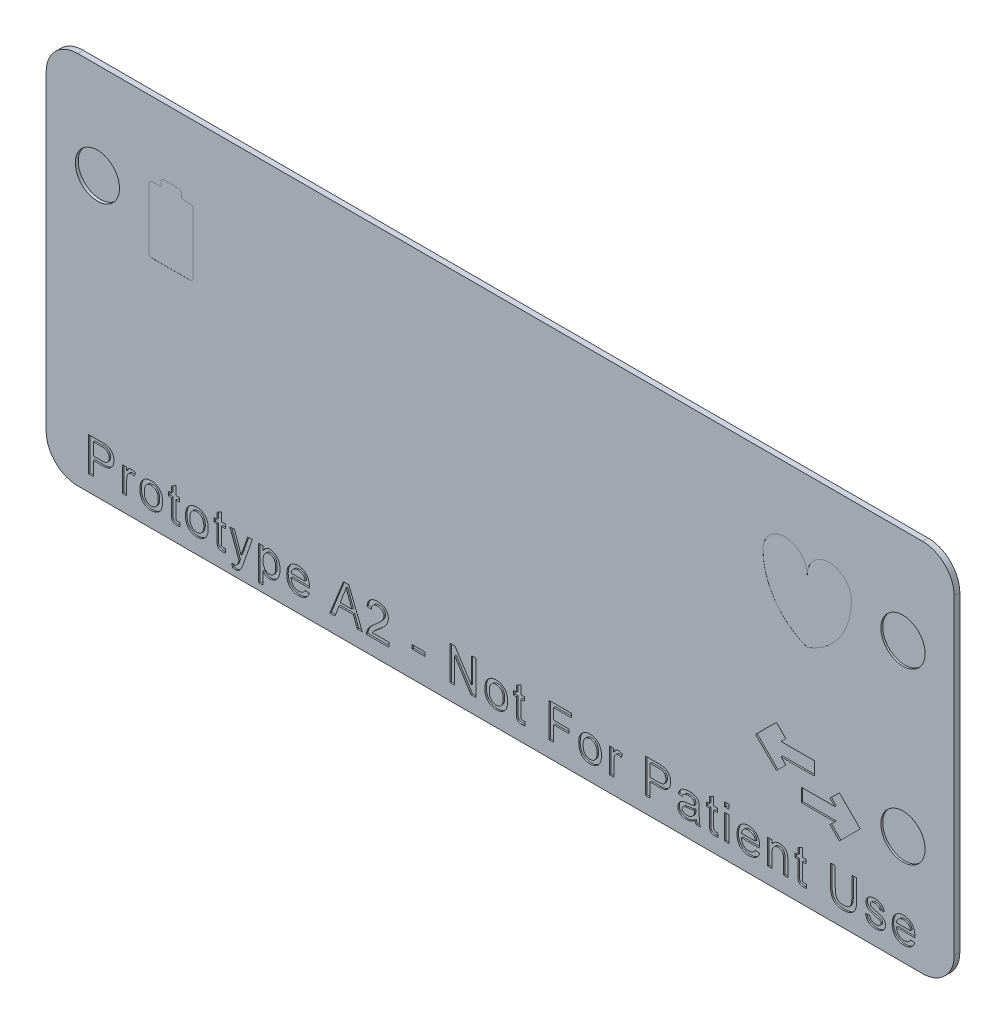
SolidWorks part; units mm, degrees
material "PC High Viscosity"
ref_plane "Front" through (0, 0, 0) normal (0, 0, 1) x (1, 0, 0)
ref_plane "Top" through (0, 0, 0) normal (0, 1, 0) x (1, 0, 0)
ref_plane "Right" through (0, 0, 0) normal (1, 0, 0) x (0, 0, -1)
sketch "Sketch1" plane through (0, 0, 0) normal (0, 0, 1) x (1, 0, 0)
  line L1 (2.14, 0) -> (59.46, 0)
  line L2 (0, 2.14) -> (0, 23.26)
  line L3 (2.14, 25.4) -> (59.46, 25.4)
  line L4 (61.6, 2.14) -> (61.6, 23.26)
  arc A0 (2.14, 0) -> (0, 2.14) centre (2.14, 2.14) cw
  arc A1 (59.46, 0) -> (61.6, 2.14) centre (59.46, 2.14) ccw
  arc A2 (61.6, 23.26) -> (59.46, 25.4) centre (59.46, 23.26) ccw
  arc A3 (2.14, 25.4) -> (0, 23.26) centre (2.14, 23.26) ccw
  point P7 (0, 0)
  point P12 (61.6, 25.4)
  point P15 (0, 25.4)
  dimension "D3" = 2.14
  dimension "D1" = 61.6
  dimension "D2" = 25.4
extrude "Boss-Extrude1" add sketch "Sketch1" along normal blind 0.381
sketch "Sketch2" plane through (0, 0, 0.381) normal (0, 0, 1) x (1, 0, 0)
  line L0 (30.8, 25.4) -> (30.8, 0) construction
  line L2 (2.14, 0) -> (59.46, 0) construction
  line L3 (58.125, 18.8976) -> (58.125, -4.1148) construction
  line L4 (3.475, 18.8976) -> (58.125, 18.8976) construction
  line L5 (48.5461, 7.3914) -> (55.3086, 7.3914) construction
  line L6 (3.475, 30.7351) -> (3.475, 17.3073) construction
  line L7 (59.46, 25.4) -> (2.14, 25.4) construction
  circle A1 centre (58.125, 18.8976) radius 1.5
  circle A2 centre (58.125, 7.3914) radius 1.5
  dimension "D1" = 3
  dimension "D2" = 27.325
  dimension "D3" = 7.3914
  dimension "D4" = 18.8976
  dimension "D5" = 27.325
extrude "Cut-Extrude1" cut sketch "Sketch2" against normal blind 0.127
sketch "Sketch17" plane through (0, 0, 0.381) normal (0, 0, 1) x (1, 0, 0)
  line L0 (30.8, 0) -> (30.8, 22.262) construction
  line L1 (2.14, 0) -> (59.46, 0) construction
  line L2 (58.125, 18.8976) -> (3.475, 18.8976) construction
  line L3 (3.475, 18.8976) -> (3.475, 16.2455) construction
  circle A0 centre (3.475, 18.8976) radius 1.5
  dimension "D2" = 3
  dimension "D1" = 27.325
extrude "Cut-Extrude9" cut sketch "Sketch17" against normal blind 0.2
sketch "Sketch10" plane through (0, 0, 0.381) normal (0, 0, 1) x (1, 0, 0)
  line L0 (51.625, 29.7824) -> (51.625, 19.4976) construction
  line L1 (40.6019, 17.9976) -> (41.1685, 17.9976) construction
  line L2 (43.0868, 17.9976) -> (43.716, 17.9976) construction
  line L3 (51.625, 29.2607) -> (51.625, 15.255) construction
  line L4 (50.125, 19.4976) -> (53.125, 19.4976) construction
  line L5 (48.7156, 18.8976) -> (48.207, 18.8976) construction
  line L6 (58.125, 18.8976) -> (58.125, 26.6614) construction
  arc A0 (51.625, 19.4976) -> (48.625, 19.4976) centre (50.125, 19.4976) ccw
  arc A1 (54.625, 19.4976) -> (51.625, 19.4976) centre (53.125, 19.4976) ccw
  arc A2 (48.625, 19.4976) -> (51.625, 15.255) centre (53.125, 19.4976) ccw
  arc A3 (54.625, 19.4976) -> (51.625, 15.255) centre (50.125, 19.4976) cw
  point P16 (51.625, 19.4976)
  dimension "D3" = 0.6
  dimension "D1" = 1.5
  dimension "D4" = 6.5
extrude "Heart Sym Cut-Extrude6" cut sketch "Sketch10" against normal blind 0.005
sketch "Sketch11" plane through (0, 0, 0.381) normal (0, 0, 1) x (1, 0, 0)
  line L0 (7.175, 20.3976) -> (7.775, 20.3976)
  line L1 (9.175, 20.3976) -> (9.775, 20.3976)
  line L2 (6.975, 20.1976) -> (6.975, 16.0976)
  line L3 (7.175, 15.8976) -> (9.775, 15.8976)
  line L4 (9.975, 20.1976) -> (9.975, 16.0976)
  line L5 (51.625, 15.255) -> (51.625, 14.7576) construction
  line L6 (7.775, 20.3976) -> (7.775, 20.6976)
  line L7 (7.975, 20.8976) -> (8.975, 20.8976)
  line L8 (9.175, 20.3976) -> (9.175, 20.6976)
  line L9 (8.475, 15.8976) -> (8.475, 20.8976) construction
  line L10 (3.475, 18.8976) -> (14.277, 18.8976) construction
  line L11 (8.475, 18.8976) -> (8.475, 24.0535) construction
  line L12 (6.975, 18.3976) -> (9.975, 18.3976) construction
  line L13 (3.475, 18.8976) -> (3.475, 18.4021) construction
  arc A0 (9.975, 16.0976) -> (9.775, 15.8976) centre (9.775, 16.0976) cw
  arc A1 (7.175, 15.8976) -> (6.975, 16.0976) centre (7.175, 16.0976) cw
  arc A2 (9.975, 20.1976) -> (9.775, 20.3976) centre (9.775, 20.1976) ccw
  arc A3 (6.975, 20.1976) -> (7.175, 20.3976) centre (7.175, 20.1976) cw
  arc A4 (9.175, 20.6976) -> (8.975, 20.8976) centre (8.975, 20.6976) ccw
  arc A5 (7.775, 20.6976) -> (7.975, 20.8976) centre (7.975, 20.6976) cw
  point P13 (8.475, 20.8976)
  point P32 (8.475, 18.3976)
  dimension "D1" = 0.2
  dimension "D2" = 0.2
  dimension "D3" = 0.5
  dimension "D4" = 5
  dimension "D5" = 3
  dimension "D7" = 1
  dimension "D8" = 0.5
extrude "Batt Sym Cut-Extrude7" cut sketch "Sketch11" against normal blind 0.005
sketch "Sketch12" plane through (0, 0, 0.381) normal (0, 0, 1) x (1, 0, 0)
  line L0 (50.8438, 7.6414) -> (50.1126, 8.3266)
  line L1 (50.1126, 8.3266) -> (50.4545, 8.6914)
  line L2 (50.4545, 8.6914) -> (51.8418, 7.3914)
  line L3 (51.8418, 7.3914) -> (50.4545, 6.0914)
  line L4 (50.8438, 7.1414) -> (49.3082, 7.1414)
  line L5 (49.3082, 7.1414) -> (49.3082, 7.6414)
  line L6 (49.3082, 7.6414) -> (50.8438, 7.6414)
  line L7 (50.8438, 7.1414) -> (50.1126, 6.4562)
  line L8 (50.1126, 6.4562) -> (50.4545, 6.0914)
  line L9 (52.3439, 8.3266) -> (53.3418, 7.3914)
  line L10 (49.3082, 7.3914) -> (54.9418, 7.3914) construction
  line L11 (52.6858, 6.0914) -> (53.8062, 7.1414)
  line L12 (52.3439, 8.3266) -> (52.6858, 8.6914)
  line L13 (52.6858, 8.6914) -> (53.8062, 7.6414)
  line L14 (52.3439, 6.4562) -> (39.6866, 6.4562) construction
  line L15 (52.3439, 6.4562) -> (52.6858, 6.0914)
  line L16 (53.8062, 7.1414) -> (54.9418, 7.1414)
  line L17 (54.9418, 7.1414) -> (54.9418, 7.6414)
  line L18 (54.9418, 7.6414) -> (53.8062, 7.6414)
  line L19 (52.3439, 6.4562) -> (53.3418, 7.3914)
  line L20 (52.6858, 6.0914) -> (42.4342, 6.0914) construction
  line L21 (52.6858, 8.6914) -> (41.7541, 8.6914) construction
  line L22 (58.125, 7.3914) -> (51.4424, 7.3914) construction
  line L23 (52.125, 7.3914) -> (52.125, 18.9676) construction
  line L24 (58.125, 7.3914) -> (58.125, 18.9676) construction
  line L25 (51.8418, 7.3914) -> (51.8418, 21.5786) construction
  line L26 (49.3082, 21.1893) -> (49.3082, 21.9616) construction
  line L27 (45.5349, 20.0944) -> (45.5349, 19.113) construction
  dimension "D1" = 0.5
  dimension "D2" = 0.5
  dimension "D3" = 0.5
  dimension "D4" = 1.3
  dimension "D5" = 1.3
  dimension "D6" = 1.5
  dimension "D7" = 1.6
  dimension "D8" = 6
  dimension "D9" = 1.5356
extrude "Cut-Extrude8" [suppressed] cut sketch "Sketch12" against normal blind 0.005
sketch "Sketch13" plane through (0, 0, 0.381) normal (0, 0, 1) x (1, 0, 0)
  line L0 (53.8108, 7.8056) -> (53.1744, 7.1692)
  line L1 (53.1744, 7.1692) -> (53.5022, 6.8414)
  line L2 (58.125, 7.3914) -> (42.91, 7.3914) construction
  line L3 (58.125, 7.3914) -> (58.125, 23.6089) construction
  line L11 (52.125, 8.3914) -> (48.125, 8.3914) construction
  line L12 (49.8478, 7.9414) -> (50.1756, 7.6136)
  line L13 (48.125, 8.3914) -> (49.5392, 6.9772)
  line L15 (51.225, 6.3914) -> (55.225, 6.3914) construction
  line L18 (51.225, 5.9414) -> (53.5022, 5.9414)
  line L19 (51.225, 6.8414) -> (51.225, 5.9414)
  line L20 (53.5022, 6.8414) -> (51.225, 6.8414)
  line L22 (55.225, 6.3914) -> (53.8108, 7.8056)
  line L23 (53.1744, 5.6136) -> (53.8108, 4.9772)
  line L25 (55.225, 6.3914) -> (53.8108, 4.9772)
  line L26 (53.5022, 5.9414) -> (53.1744, 5.6136)
  line L31 (50.1756, 7.6136) -> (49.5392, 6.9772)
  line L33 (48.125, 8.3914) -> (49.5392, 9.8056)
  line L34 (49.8478, 8.8414) -> (52.125, 8.8414)
  line L35 (52.125, 8.8414) -> (52.125, 7.9414)
  line L36 (52.125, 7.9414) -> (49.8478, 7.9414)
  line L37 (49.8478, 8.8414) -> (50.1756, 9.1692)
  line L38 (50.1756, 9.1692) -> (49.5392, 9.8056)
  point P15 (51.225, 6.3914)
  dimension "D2" = 0.9
  dimension "D3" = 1
  dimension "D4" = 6
  dimension "D5" = 1
  dimension "D6" = 45
  dimension "D7" = 45
  dimension "D8" = 0.9
  dimension "D9" = 2
  dimension "D10" = 0.9
  dimension "D12" = 45
  dimension "D14" = 2
  dimension "D16" = 4
  dimension "D17" = 4
extrude "Comm SymCut-Extrude9" cut sketch "Sketch13" against normal blind 0.1
sketch "Sketch18" plane through (0, 0, 0.381) normal (0, 0, 1) x (1, 0, 0)
  line L0 (2.6113, 1.0737) -> (59.315, 1.0737) construction
sketch "Sketch16" plane through (0, 0, 0.381) normal (0, 0, 1) x (1, 0, 0)
  line L0 (72.8522, -45.5346) -> (327.5189, -45.5346) construction
  text T0 "Prototype A2 - Not For Patient Use" font "Arial" height in points 9
extrude "Cut-Extrude10" cut sketch "Sketch16" against normal blind 0.1
